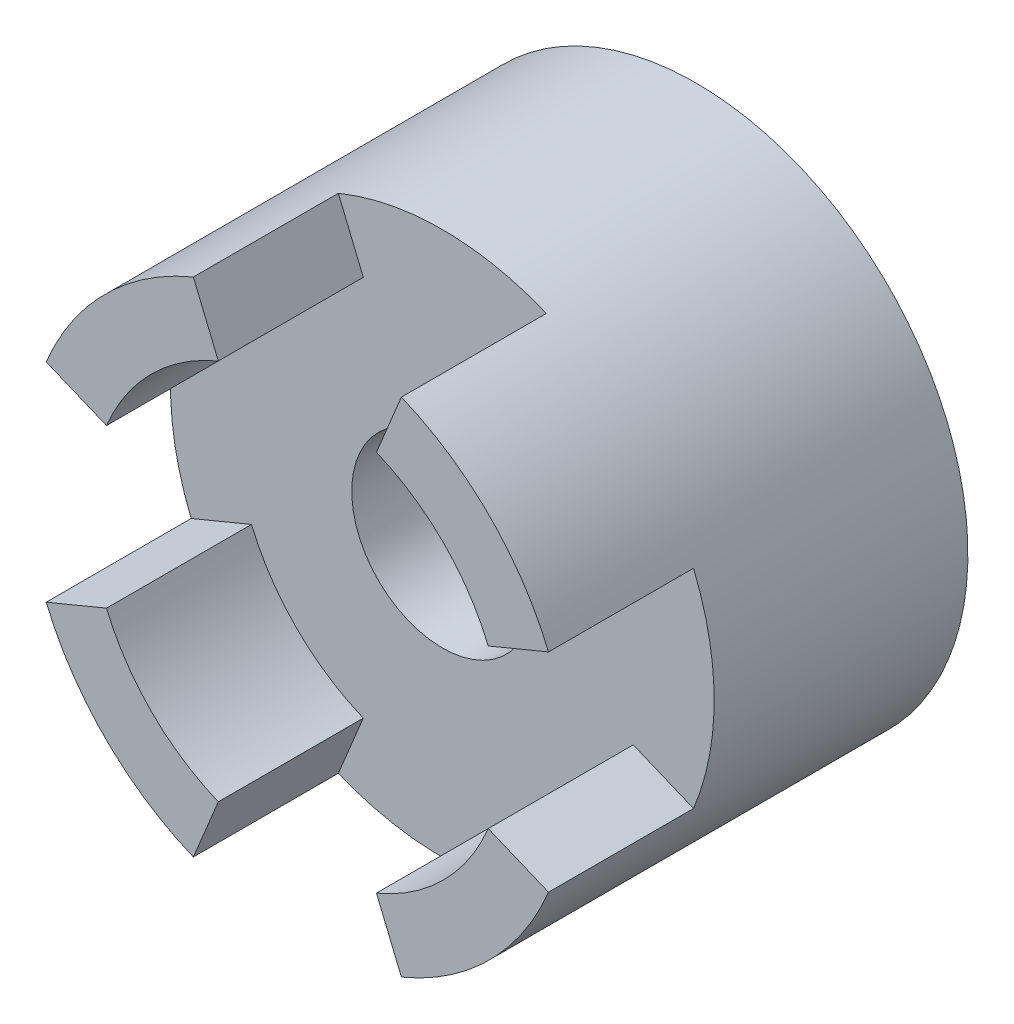
SolidWorks part; units mm, degrees
ref_plane "Front Plane" through (0, 0, 0) normal (0, 0, 1) x (1, 0, 0)
ref_plane "Top Plane" through (0, 0, 0) normal (0, 1, 0) x (1, 0, 0)
ref_plane "Right Plane" through (0, 0, 0) normal (1, 0, 0) x (0, 0, -1)
sketch "Sketch1" plane through (0, 0, 0) normal (0, 0, 1) x (1, 0, 0)
  circle A0 centre (0, 0) radius 19.05
  circle A1 centre (0, 0) radius 14.478
  dimension "D1" = 38.1
  dimension "D2" = 28.956
extrude "Boss-Extrude1" add sketch "Sketch1" against normal blind 38.1 contours A0 A1
sketch "Sketch2" plane through (0, 0, 0) normal (0, 0, 1) x (1, 0, 0)
  circle A0 centre (0, 0) radius 6.35
  circle A1 centre (0, 0) radius 14.478
  circle A2 centre (0, 0) radius 14.478 construction
  dimension "D1" = 12.7
extrude "Boss-Extrude2" add sketch "Sketch2" along direction (0, 0, 1) on the side against the normal up to surface (27.94 mm away) from offset 10.16 offset against normal yes
sketch "Sketch3" plane through (0, 0, 0) normal (0, 0, 1) x (1, 0, 0)
  line L0 (-5.5405, 13.3759) -> (-7.2901, 17.5999)
  line L1 (5.5405, 13.3759) -> (7.2901, 17.5999)
  line L2 (0, 0) -> (-7.2901, 17.5999) construction
  line L3 (0, 0) -> (5.5405, 13.3759) construction
  line L4 (0, 0) -> (0, 19.05) construction
  line L5 (13.3759, 5.5405) -> (17.5999, 7.2901)
  line L6 (13.3759, -5.5405) -> (17.5999, -7.2901)
  line L7 (5.5405, -13.3759) -> (7.2901, -17.5999)
  line L8 (-5.5405, -13.3759) -> (-7.2901, -17.5999)
  line L9 (-13.3759, -5.5405) -> (-17.5999, -7.2901)
  line L10 (-13.3759, 5.5405) -> (-17.5999, 7.2901)
  arc A0 (-5.5405, 13.3759) -> (5.5405, 13.3759) centre (0, 0) cw
  arc A1 (13.3759, 5.5405) -> (13.3759, -5.5405) centre (0, 0) cw
  arc A2 (-7.2901, 17.5999) -> (7.2901, 17.5999) centre (0, 0) cw
  arc A3 (17.5999, 7.2901) -> (17.5999, -7.2901) centre (0, 0) cw
  circle A4 centre (0, 0) radius 19.05 construction
  arc A5 (5.5405, -13.3759) -> (-5.5405, -13.3759) centre (0, 0) cw
  arc A6 (7.2901, -17.5999) -> (-7.2901, -17.5999) centre (0, 0) cw
  circle A7 centre (0, 0) radius 14.478 construction
  arc A8 (-13.3759, -5.5405) -> (-13.3759, 5.5405) centre (0, 0) cw
  arc A9 (-17.5999, -7.2901) -> (-17.5999, 7.2901) centre (0, 0) cw
  point P24 (0, 0)
  dimension "D3" = 4
  dimension "D1" = 45
  dimension "D2" = 22.5
extrude "Cut-Extrude1" cut sketch "Sketch3" against normal blind 10.16
sketch "Sketch4" plane through (0, 0, -38.1) normal (0, 0, -1) x (-1, 0, 0)
  circle A0 centre (0, 0) radius 6.35
  circle A1 centre (0, 0) radius 19.05
  circle A2 centre (0, 0) radius 6.35 construction
  circle A3 centre (0, 0) radius 19.05 construction
extrude "Cut-Extrude2" cut sketch "Sketch4" against normal blind 10.16
